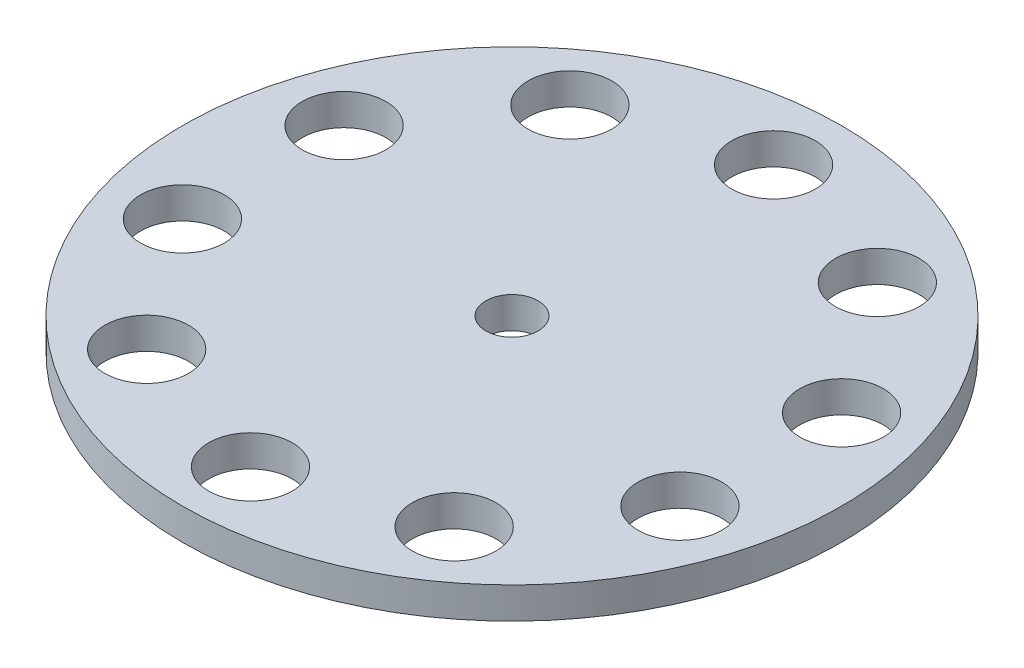
SolidWorks part; units mm, degrees
material "Beech"
ref_plane "Front Plane" through (0, 0, 0) normal (0, 0, 1) x (1, 0, 0)
ref_plane "Top Plane" through (0, 0, 0) normal (0, 1, 0) x (1, 0, 0)
ref_plane "Right Plane" through (0, 0, 0) normal (1, 0, 0) x (0, 0, -1)
sketch "Sketch1" plane through (0, 0, 0) normal (0, 1, 0) x (1, 0, 0)
  circle A0 centre (0, 0) radius 31.5
  circle A1 centre (0, 25) radius 4
  circle A2 centre (14.6946, 20.2254) radius 4
  circle A3 centre (23.7764, 7.7254) radius 4
  circle A4 centre (23.7764, -7.7254) radius 4
  circle A5 centre (14.6946, -20.2254) radius 4
  circle A6 centre (0, -25) radius 4
  circle A7 centre (-14.6946, -20.2254) radius 4
  circle A8 centre (-23.7764, -7.7254) radius 4
  circle A9 centre (-23.7764, 7.7254) radius 4
  circle A10 centre (-14.6946, 20.2254) radius 4
  circle A11 centre (0, 0) radius 2.5
  point P25 (0, 0)
  dimension "D1" = 63
  dimension "D3" = 8
  dimension "D5" = 5
  dimension "D2" = 25
  dimension "D4" = 10
extrude "Boss-Extrude1" add sketch "Sketch1" along normal blind 3
